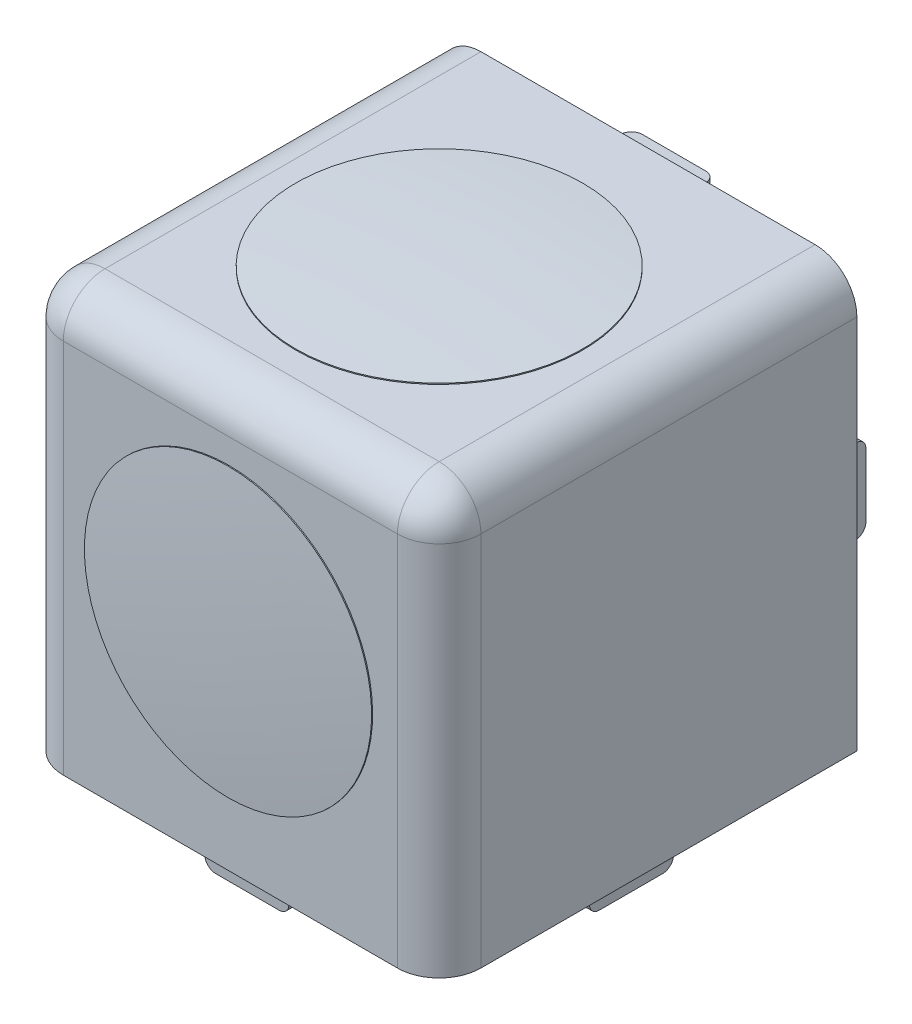
SolidWorks part; units mm, degrees
ref_plane "Front Plane" through (0, 0, 0) normal (0, 0, 1) x (1, 0, 0)
ref_plane "Top Plane" through (0, 0, 0) normal (0, 1, 0) x (1, 0, 0)
ref_plane "Right Plane" through (0, 0, 0) normal (1, 0, 0) x (0, 0, -1)
sketch "Sketch1" plane through (0, 0, 0) normal (0, 1, 0) x (1, 0, 0)
  line L0 (-20, -20) -> (20, -20) construction
  line L1 (-20, 0) -> (20, 0)
  line L2 (-20, 0) -> (-20, -40)
  line L3 (-20, -40) -> (20, -40)
  line L4 (20, 0) -> (20, -40)
  line L5 (0, -40) -> (0, 0) construction
  dimension "D1" = 40
extrude "Boss-Extrude1" add sketch "Sketch1" along normal blind 40
sketch "Sketch2" plane through (0, 0, 0) normal (1, 0, 0) x (0, 0, -1)
  line L0 (0, 20) -> (-40, 20) construction
  line L1 (-40, 20) -> (-40, 33)
  line L2 (-40, 32) -> (-19.7234, 31.469) construction
  line L3 (-7.4, 28) -> (-3.5, 24.25)
  line L4 (-3.5, 24.25) -> (0, 24.25)
  line L5 (0, 24.25) -> (0, 20)
  line L6 (0, 40) -> (0, 0) construction
  line L7 (-40, 40) -> (-40, 0) construction
  line L8 (-40, 20) -> (0, 20)
  line L9 (-39.2552, 32.2552) -> (-40, 33)
  line L10 (-19.7234, 31.469) -> (-38.5743, 31.9627)
  line L11 (-7.4, 28) -> (-11.8, 28)
  arc A0 (-38.5743, 31.9627) -> (-39.2552, 32.2552) centre (-38.5481, 32.9623) cw
  arc A1 (-11.8, 28) -> (-19.7234, 31.469) centre (-20.0237, 20) ccw
  point P2 (-20, 20)
  dimension "D4" = 1
  dimension "D1" = 1.5
  dimension "D2" = 24
  dimension "D3" = 1
  dimension "D5" = 45
  dimension "D6" = 8.5
  dimension "D7" = 3.5
  dimension "D8" = 3.9
  dimension "D9" = 16
  dimension "D10" = 4.4
revolve "Cut-Revolve1" cut sketch "Sketch2" angle 360 mid plane about L0
sketch "Sketch3" plane through (0, 0, 0) normal (0, 0, -1) x (-1, 0, 0)
  line L0 (-18.5, 20) -> (0, 20) construction
  line L1 (-4.1, 38.5) -> (4.1, 38.5)
  line L2 (-4.1, 38.5) -> (-4.1, 36.3)
  line L3 (-4.1, 36.3) -> (4.1, 36.3)
  line L4 (4.1, 38.5) -> (4.1, 36.3)
  line L5 (-18.5, 24.1) -> (-16.3, 24.1)
  line L6 (-18.5, 24.1) -> (-18.5, 15.9)
  line L7 (-18.5, 15.9) -> (-16.3, 15.9)
  line L8 (-16.3, 24.1) -> (-16.3, 15.9)
  line L9 (16.3, 24.1) -> (18.5, 24.1)
  line L10 (16.3, 24.1) -> (16.3, 15.9)
  line L11 (16.3, 15.9) -> (18.5, 15.9)
  line L12 (18.5, 24.1) -> (18.5, 15.9)
  line L13 (0, 20) -> (18.5, 20) construction
  line L14 (0, 20) -> (0, 38.5) construction
  line L15 (-20, 40) -> (20, 40) construction
  dimension "D1" = 8.2
  dimension "D2" = 2.2
  dimension "D3" = 1.5
extrude "Boss-Extrude2" add sketch "Sketch3" along normal blind 2.5 draft 3
fillet "Fillet1" radius 1 6 edges at (17.4, 23.969, -2.5) (17.4, 16.031, -2.5) (-17.4, 16.031, -2.5) (-17.4, 23.969, -2.5) (-3.969, 37.4, -2.5) (3.969, 37.4, -2.5)
sketch "Sketch4" plane through (0, 0, 0) normal (0, 0, -1) x (-1, 0, 0)
  line L0 (-4.1, 36.3) -> (4.1, 36.3) construction
  line L1 (-4, 36.3) -> (4, 36.3)
  line L2 (-4, 36.3) -> (-4, 34.3)
  line L3 (-4, 34.3) -> (4, 34.3)
  line L4 (4, 36.3) -> (4, 34.3)
  line L5 (-16.3, 24) -> (-14.3, 24)
  line L6 (-16.3, 24) -> (-16.3, 16)
  line L7 (-16.3, 16) -> (-14.3, 16)
  line L8 (-14.3, 24) -> (-14.3, 16)
  line L9 (14.3, 24) -> (16.3, 24)
  line L10 (14.3, 24) -> (14.3, 16)
  line L11 (14.3, 16) -> (16.3, 16)
  line L12 (16.3, 24) -> (16.3, 16)
  line L13 (-16.3, 15.9) -> (-16.3, 24.1) construction
  line L14 (16.3, 24.1) -> (16.3, 15.9) construction
  line L15 (-16.3, 20) -> (0, 20) construction
  line L16 (0, 20) -> (16.3, 20) construction
  line L17 (0, 20) -> (0, 36.3) construction
  dimension "D1" = 8
  dimension "D2" = 2
extrude "Cut-Extrude1" [suppressed] cut sketch "Sketch4" against normal blind 1.5 draft 3
fillet "Fillet2" [suppressed] radius 0.3
ref_plane "Plane1" through (0, 0, 0) normal (0, 0.7071, -0.7071) x (-1, 0, 0)
mirror "Mirror1" about plane through (0, 0, 0) normal (0, 0.7071, -0.7071) of "Fillet2", "Cut-Extrude1", "Cut-Revolve1", "Boss-Extrude2", "Fillet1"
sketch "Sketch5" plane through (0, 0, 0) normal (0, 0, -1) x (-1, 0, 0)
  line L1 (5.25, 10.5) -> (-5.25, 10.5)
  line L2 (5.25, 10.5) -> (5.25, 0)
  line L3 (5.25, 0) -> (-5.25, 0)
  line L4 (-5.25, 10.5) -> (-5.25, 0)
  dimension "D1" = 10.5
  dimension "D2" = 10.5
extrude "Cut-Extrude2" cut sketch "Sketch5" against normal blind 10.5
fillet "Fillet3" radius 1 5 edges at (5.25, 10.5, 5.25) (0, 10.5, 10.5) (-5.25, 10.5, 5.25) (5.25, 5.25, 10.5) (-5.25, 5.25, 10.5)
fillet "Fillet4" radius 4 5 edges at (0, 40, 40) (20, 20, 40) (20, 40, 20) (-20, 40, 20) (-20, 20, 40)
sketch "Sketch6" plane through (0, 0, 0) normal (1, 0, 0) x (0, 0, -1)
  line L0 (0, 20) -> (-40.725, 20) construction
  line L2 (-40.725, 20) -> (-38.875, 20)
  line L3 (-40.225, 33.75) -> (-40.125, 33.75)
  line L4 (-40.125, 33.75) -> (-40.125, 31.975)
  line L5 (-40.125, 31.975) -> (-36.125, 31.975)
  line L6 (-38.875, 20) -> (-38.875, 30.725)
  line L7 (-38.875, 30.725) -> (-36.125, 30.725)
  line L8 (-36.125, 30.725) -> (-36.125, 31.975)
  line L9 (-40, 20) -> (-40, 33) construction
  arc A0 (-40.725, 20) -> (-40.225, 33.75) centre (148.5875, 20) cw
  dimension "D1" = 4
  dimension "D2" = 0.6
  dimension "D3" = 1.25
  dimension "D4" = 0.125
  dimension "D5" = 0.025
  dimension "D6" = 1.25
  dimension "D7" = 0.5
  dimension "D8" = 0.75
revolve "Revolve1" add sketch "Sketch6" angle 360 mid plane about L0
mirror "Mirror2" about plane through (0, 0, 0) normal (0, 0.7071, -0.7071) of bodies 151
